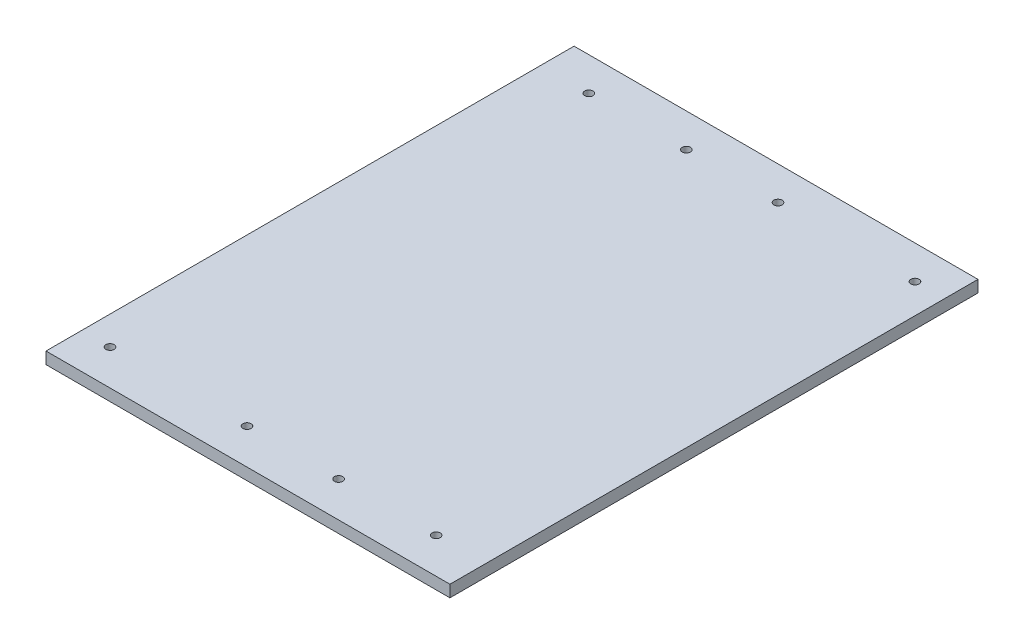
SolidWorks part; units mm, degrees
material "Acrílico (médio-alto impacto)"
ref_plane "Front Plane" through (0, 0, 0) normal (0, 0, 1) x (1, 0, 0)
ref_plane "Top Plane" through (0, 0, 0) normal (0, 1, 0) x (1, 0, 0)
ref_plane "Right Plane" through (0, 0, 0) normal (1, 0, 0) x (0, 0, -1)
sketch "Esboço1" plane through (0, 0, 0) normal (0, -1, 0) x (1, 0, 0)
  line L1 (-102.5, -134) -> (102.5, -134)
  line L2 (-102.5, -134) -> (-102.5, 134)
  line L20 (-102.5, 134) -> (102.5, 134)
  line L21 (102.5, -134) -> (102.5, 134)
  line L22 (-102.5, -134) -> (102.5, 134) construction
  line L23 (-102.5, 134) -> (102.5, -134) construction
  point P0 (0, 0)
  dimension "D1" = 268
  dimension "D2" = 205
extrude "Ressalto-extrusão1" add sketch "Esboço1" against normal blind 6
hole_wizard "Furo de diâmetro Ø4.0 (4)1" positions "Esboço2" profile "Esboço3" hole size "Ø4.2" standard "ISO" end condition through all
sketch "Esboço2" plane through (0, 0, 0) normal (0, -1, 0) x (-1, 0, 0)
  point P0 (-87.5, 117)
  point P3 (-18, 117)
  point P6 (-77.5, -116)
  point P9 (-28, -116)
  point P12 (18.5, -116)
  point P15 (88, -116)
  point P18 (28.5, 117)
  point P21 (78, 117)
sketch "Esboço3" plane through (87.5, 0, -117) normal (1, 0, 0) x (0, 0, -1)
  line L0 (0, 0) -> (0, 6)
  line L1 (0, 6) -> (2.1, 6)
  line L2 (2.1, 6) -> (2.1, 0)
  line L5 (2.1, 0) -> (0, 0)
  line L11 (0, -6.35) -> (0, 107.95) construction
  dimension "Thru Hole Dia." = 4.2
  dimension "Thru Hole Depth" = 6
